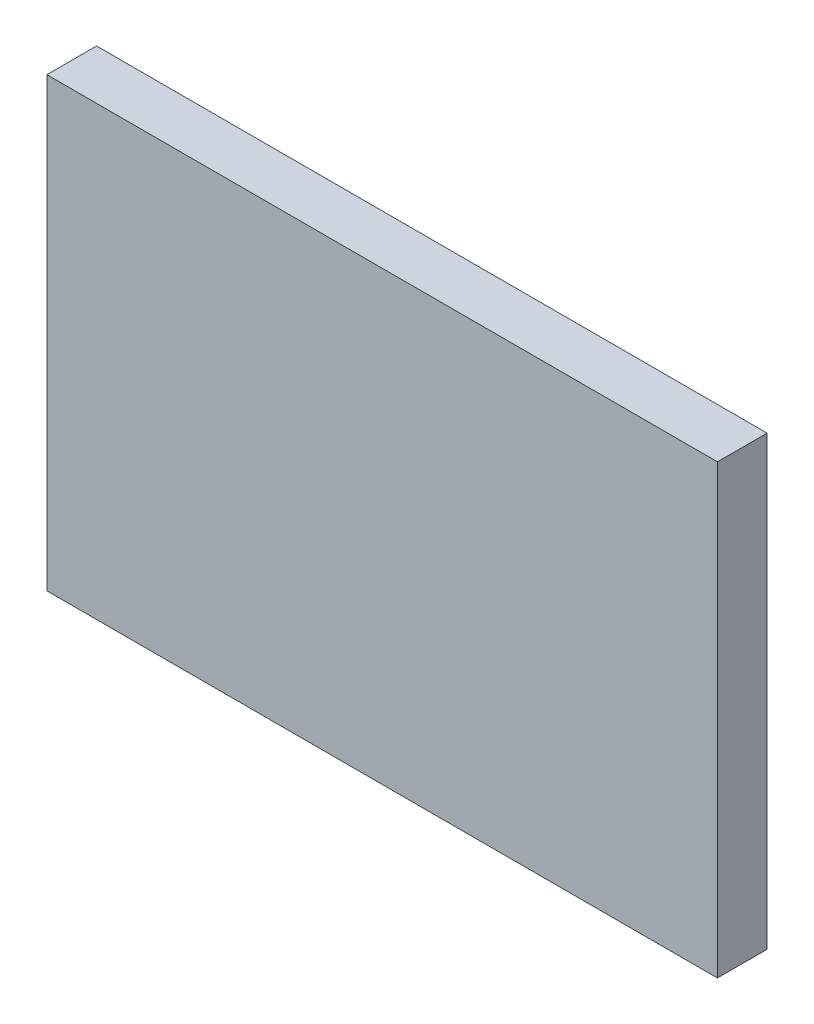
SolidWorks part; units mm, degrees
ref_plane "Front Plane" through (0, 0, 0) normal (0, 0, 1) x (1, 0, 0)
ref_plane "Top Plane" through (0, 0, 0) normal (0, 1, 0) x (1, 0, 0)
ref_plane "Right Plane" through (0, 0, 0) normal (1, 0, 0) x (0, 0, -1)
sketch "Sketch1" plane through (0, 0, 0) normal (1, 0, 0) x (0, 0, -1)
  line L1 (0, 0) -> (101.6, 0)
  line L2 (0, 0) -> (0, 914.4)
  line L3 (0, 914.4) -> (101.6, 914.4)
  line L4 (101.6, 0) -> (101.6, 914.4)
  dimension "D1" = 914.4
  dimension "D2" = 101.6
extrude "Base" add sketch "Sketch1" along normal blind 1371.6
